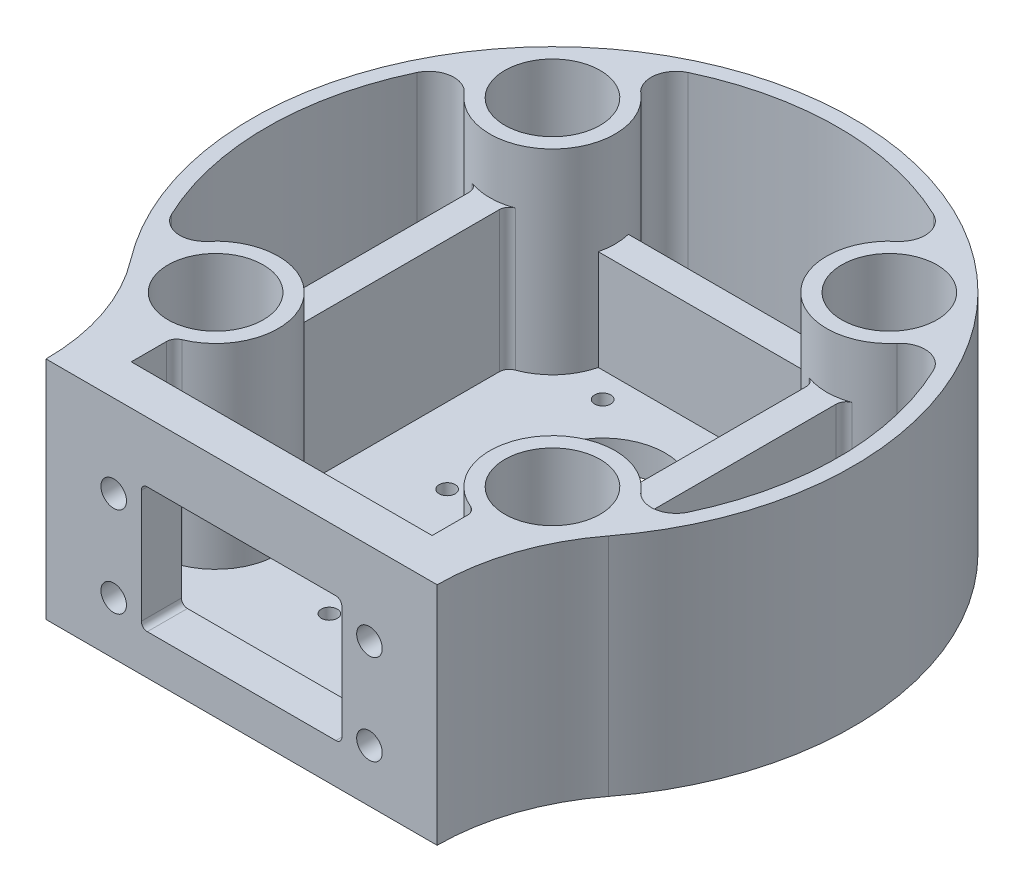
SolidWorks part; units mm, degrees
ref_plane "Front Plane" through (0, 0, 0) normal (0, 0, 1) x (1, 0, 0)
ref_plane "Top Plane" through (0, 0, 0) normal (0, 1, 0) x (1, 0, 0)
ref_plane "Right Plane" through (0, 0, 0) normal (1, 0, 0) x (0, 0, -1)
sketch "Sketch1" plane through (0, 0, 0) normal (0, 1, 0) x (1, 0, 0)
  line L0 (0, 0) -> (0, -60) construction
  line L1 (0, 0) -> (-33.5876, -33.5876) construction
  line L2 (-39, -62) -> (39, -62)
  line L3 (-30, -54) -> (30, -54)
  line L4 (-30, -45.5617) -> (-30, -54)
  line L5 (30, -54) -> (30, -45.5617)
  line L6 (-39, -54) -> (39, -54) construction
  arc A0 (47.6471, -36.4658) -> (-47.6471, -36.4658) centre (0, 0) ccw
  circle A1 centre (-33.5876, -33.5876) radius 9.5
  arc A2 (-33.5402, -46.0875) -> (-46.0875, -33.5402) centre (-33.5876, -33.5876) ccw
  arc A3 (-33.5402, -46.0875) -> (-30, -48.4665) centre (0, 0) ccw
  circle A4 centre (-33.5876, -33.5876) radius 12.5 construction
  circle A5 centre (0, 0) radius 57 construction
  arc A6 (-46.0875, 33.5402) -> (-33.5402, 46.0875) centre (-33.5876, 33.5876) ccw
  circle A7 centre (-33.5876, 33.5876) radius 9.5
  arc A8 (33.5402, 46.0875) -> (46.0875, 33.5402) centre (33.5876, 33.5876) ccw
  circle A9 centre (33.5876, 33.5876) radius 9.5
  arc A10 (46.0875, -33.5402) -> (33.5402, -46.0875) centre (33.5876, -33.5876) ccw
  circle A11 centre (33.5876, -33.5876) radius 9.5
  arc A12 (-46.0875, 33.5402) -> (-46.0875, -33.5402) centre (0, 0) ccw
  arc A13 (33.5402, 46.0875) -> (-33.5402, 46.0875) centre (0, 0) ccw
  arc A14 (46.0875, -33.5402) -> (46.0875, 33.5402) centre (0, 0) ccw
  arc A15 (-39, -62) -> (-47.6471, -36.4658) centre (-81, -61.9919) ccw
  arc A16 (39, -62) -> (47.6471, -36.4658) centre (81, -61.9919) cw
  circle A17 centre (0, 0) radius 60 construction
  arc A19 (30, -48.4665) -> (33.5402, -46.0875) centre (0, 0) ccw
  dimension "D1" = 120
  dimension "D4" = 19
  dimension "D11" = 42
  dimension "D12" = 42
  dimension "D2" = 45
  dimension "D3" = 47.5
  dimension "D8" = 62
  dimension "D9" = 78
  dimension "D10" = 39
  dimension "D14" = 60
  dimension "D15" = 30
  dimension "D5" = 3
  dimension "D6" = 3
  dimension "D13" = 8
  dimension "D7" = 4
extrude "Boss-Extrude1" add sketch "Sketch1" along normal blind 45 contours L2 A16 A0 A15 A19 L5 L3 L4 A3 A2 A12 A6 A13 A8 A14 A10 A1 A7 A9 A11 | L5 A19 A10 | A2 A3 L4
sketch "Sketch2" plane through (0, 0, 0) normal (0, -1, 0) x (1, 0, 0)
  line L1 (39, 62) -> (-39, 62)
  line L2 (39, 62) -> (-39, 62)
  arc A3 (-47.6471, 36.4658) -> (-39, 62) centre (-81, 61.9919) ccw
  arc A4 (-47.6471, 36.4658) -> (47.6471, 36.4658) centre (0, 0) ccw
  arc A5 (39, 62) -> (47.6471, 36.4658) centre (81, 61.9919) ccw
  arc A6 (-47.6471, 36.4658) -> (-39, 62) centre (-81, 61.9919) ccw
  arc A7 (-47.6471, 36.4658) -> (47.6471, 36.4658) centre (0, 0) ccw
  arc A8 (39, 62) -> (47.6471, 36.4658) centre (81, 61.9919) ccw
  dimension "D1" = 0
extrude "Boss-Extrude2" add sketch "Sketch2" against normal blind 6
sketch "Sketch3" plane through (0, 6, 0) normal (0, 1, 0) x (1, 0, 0)
  line L1 (-5.75, -38.75) -> (5.75, -38.75) construction
  line L2 (-5.75, -38.75) -> (-5.75, -27.25) construction
  line L3 (-5.75, -27.25) -> (5.75, -27.25) construction
  line L4 (5.75, -38.75) -> (5.75, -27.25) construction
  line L5 (-5.75, -38.75) -> (5.75, -27.25) construction
  line L6 (-5.75, -27.25) -> (5.75, -38.75) construction
  circle A0 centre (-33.5876, 33.5876) radius 5.25
  circle A1 centre (33.5876, 33.5876) radius 5.25
  circle A2 centre (33.5876, -33.5876) radius 5.25
  circle A3 centre (-33.5876, -33.5876) radius 5.25
  circle A4 centre (0, -33) radius 4.25
  circle A5 centre (-5.75, -27.25) radius 1.6
  circle A6 centre (5.75, -27.25) radius 1.6
  circle A7 centre (5.75, -38.75) radius 1.6
  circle A8 centre (-5.75, -38.75) radius 1.6
  dimension "D1" = 10.5
  dimension "D2" = 10.5
  dimension "D3" = 10.5
  dimension "D4" = 10.5
  dimension "D6" = 8.5
  dimension "D9" = 3.2
  dimension "D10" = 3.2
  dimension "D11" = 3.2
  dimension "D12" = 3.2
  dimension "D5" = 33
  dimension "D7" = 11.5
  dimension "D8" = 11.5
extrude "Cut-Extrude1" cut sketch "Sketch3" against normal through all
fillet "Fillet1" radius 5 6 edges at (-46.0875, 25.5, 33.5402) (46.0875, 25.5, 33.5402) (46.0875, 25.5, -33.5402) (33.5402, 25.5, -46.0875) (-33.5402, 25.5, -46.0875) (-46.0875, 25.5, -33.5402)
sketch "Sketch4" plane through (0, 6, 0) normal (0, 1, 0) x (1, 0, 0)
  circle A0 centre (0, -33) radius 5.1
  dimension "D1" = 10.2
extrude "Cut-Extrude2" cut sketch "Sketch4" against normal blind 2
sketch "Sketch5" plane through (0, 0, 0) normal (0, -1, 0) x (1, 0, 0)
  line L1 (-15.5, 5.5) -> (15.5, 5.5) construction
  line L2 (-15.5, 5.5) -> (-15.5, -25.5) construction
  line L3 (-15.5, -25.5) -> (15.5, -25.5) construction
  line L4 (15.5, 5.5) -> (15.5, -25.5) construction
  line L5 (-15.5, 5.5) -> (15.5, -25.5) construction
  line L6 (-15.5, -25.5) -> (15.5, 5.5) construction
  circle A0 centre (0, -10) radius 12.5
  circle A1 centre (15.5, 5.5) radius 1.6
  circle A2 centre (-15.5, 5.5) radius 1.6
  circle A3 centre (-15.5, -25.5) radius 1.6
  circle A4 centre (15.5, -25.5) radius 1.6
  dimension "D2" = 25
  dimension "D5" = 3.2
  dimension "D6" = 3.2
  dimension "D7" = 3.2
  dimension "D8" = 3.2
  dimension "D1" = 10
  dimension "D3" = 31
  dimension "D4" = 31
extrude "Cut-Extrude3" cut sketch "Sketch5" against normal through all
sketch "Sketch6" plane through (0, 0, 62) normal (0, 0, 1) x (1, 0, 0)
  line L0 (-39, 0) -> (39, 0) construction
  line L1 (-20, 8) -> (20, 8)
  line L2 (-20, 8) -> (-20, 33)
  line L3 (-20, 33) -> (20, 33)
  line L4 (20, 8) -> (20, 33)
  line L5 (-20, 8) -> (20, 33) construction
  line L6 (-20, 33) -> (20, 8) construction
  point P0 (0, 20.5)
  dimension "D1" = 40
  dimension "D2" = 25
  dimension "D3" = 8
extrude "Cut-Extrude4" cut sketch "Sketch6" against normal up to next
sketch "Sketch7" plane through (0, 0, 62) normal (0, 0, 1) x (1, 0, 0)
  line L1 (-20, 33) -> (-20, 8) construction
  line L2 (20, 8) -> (20, 33) construction
  line L4 (-39, 45) -> (39, 45) construction
  circle A0 centre (-25.5, 10.5) radius 2.55
  circle A1 centre (25.5, 10.5) radius 2.55
  circle A2 centre (25.5, 28.5) radius 2.55
  circle A3 centre (-25.5, 28.5) radius 2.55
  dimension "D2" = 5.5
  dimension "D7" = 5.1
  dimension "D8" = 5.1
  dimension "D9" = 5.1
  dimension "D10" = 5.1
  dimension "D3" = 5.5
  dimension "D4" = 5.5
  dimension "D5" = 5.5
  dimension "D6" = 18
  dimension "D11" = 16.5
extrude "Cut-Extrude5" cut sketch "Sketch7" against normal up to next
sketch "Sketch8" plane through (0, 6, 0) normal (0, 1, 0) x (1, 0, 0)
  line L0 (-33.5876, 33.5876) -> (-33.5876, -33.5876) construction
  line L1 (-36.5876, 21.4529) -> (-36.5876, -21.4529)
  line L2 (-30.5876, 21.4529) -> (-30.5876, -21.4529)
  line L3 (33.5876, 33.5876) -> (33.5876, -33.5876) construction
  line L4 (30.5876, 21.4529) -> (30.5876, -21.4529)
  line L5 (36.5876, 21.4529) -> (36.5876, -21.4529)
  line L6 (-36.5876, 33.5876) -> (-36.5876, -33.5876) construction
  line L7 (-30.5876, 33.5876) -> (-30.5876, -33.5876) construction
  line L8 (30.5876, 33.5876) -> (30.5876, -33.5876) construction
  line L9 (36.5876, 33.5876) -> (36.5876, -33.5876) construction
  arc A0 (-30, -45.5617) -> (-43.1466, -25.5331) centre (-33.5876, -33.5876) ccw construction
  arc A1 (43.1466, -25.5331) -> (30, -45.5617) centre (33.5876, -33.5876) ccw construction
  arc A2 (25.5331, 43.1466) -> (43.1466, 25.5331) centre (33.5876, 33.5876) ccw construction
  arc A3 (-43.1466, 25.5331) -> (-25.5331, 43.1466) centre (-33.5876, 33.5876) ccw construction
  arc A4 (-30.5876, -21.4529) -> (-36.5876, -21.4529) centre (-33.5876, -33.5876) ccw
  arc A5 (36.5876, -21.4529) -> (30.5876, -21.4529) centre (33.5876, -33.5876) ccw
  arc A6 (30.5876, 21.4529) -> (36.5876, 21.4529) centre (33.5876, 33.5876) ccw
  arc A7 (-36.5876, 21.4529) -> (-30.5876, 21.4529) centre (-33.5876, 33.5876) ccw
  dimension "D1" = 3
  dimension "D2" = 3
  dimension "D3" = 3
  dimension "D4" = 3
extrude "Boss-Extrude3" add sketch "Sketch8" along normal blind 28
fillet "Fillet2" radius 2 10 edges at (36.5876, 20, 21.4529) (30.5876, 20, 21.4529) (-36.5876, 20, 21.4529) (-30.5876, 20, 21.4529) (30.5876, 20, -21.4529) (36.5876, 20, -21.4529) (-36.5876, 20, -21.4529) (-30.5876, 20, -21.4529) (30, 25.5, 45.5617) (-30, 25.5, 45.5617)
sketch "Sketch9" plane through (0, 6, 0) normal (0, 1, 0) x (1, 0, 0)
  line L0 (-33.5876, 33.5876) -> (33.5876, 33.5876) construction
  line L1 (-21.4529, 30.5876) -> (21.4529, 30.5876)
  line L2 (-21.4529, 36.5876) -> (21.4529, 36.5876)
  line L3 (-33.5876, 36.5876) -> (33.5876, 36.5876) construction
  line L4 (-33.5876, 30.5876) -> (33.5876, 30.5876) construction
  arc A0 (25.5331, 43.1466) -> (43.1466, 25.5331) centre (33.5876, 33.5876) ccw construction
  arc A1 (-29.2772, 21.8542) -> (-25.5331, 43.1466) centre (-33.5876, 33.5876) ccw construction
  arc A2 (21.4529, 36.5876) -> (21.4529, 30.5876) centre (33.5876, 33.5876) ccw
  arc A3 (-21.4529, 30.5876) -> (-21.4529, 36.5876) centre (-33.5876, 33.5876) ccw
  dimension "D1" = 3
  dimension "D2" = 3
extrude "Boss-Extrude4" add sketch "Sketch9" along normal blind 20
fillet "Fillet3" radius 1.2 4 edges at (20, 8, 58) (20, 33, 58) (-20, 8, 58) (-20, 33, 58)
